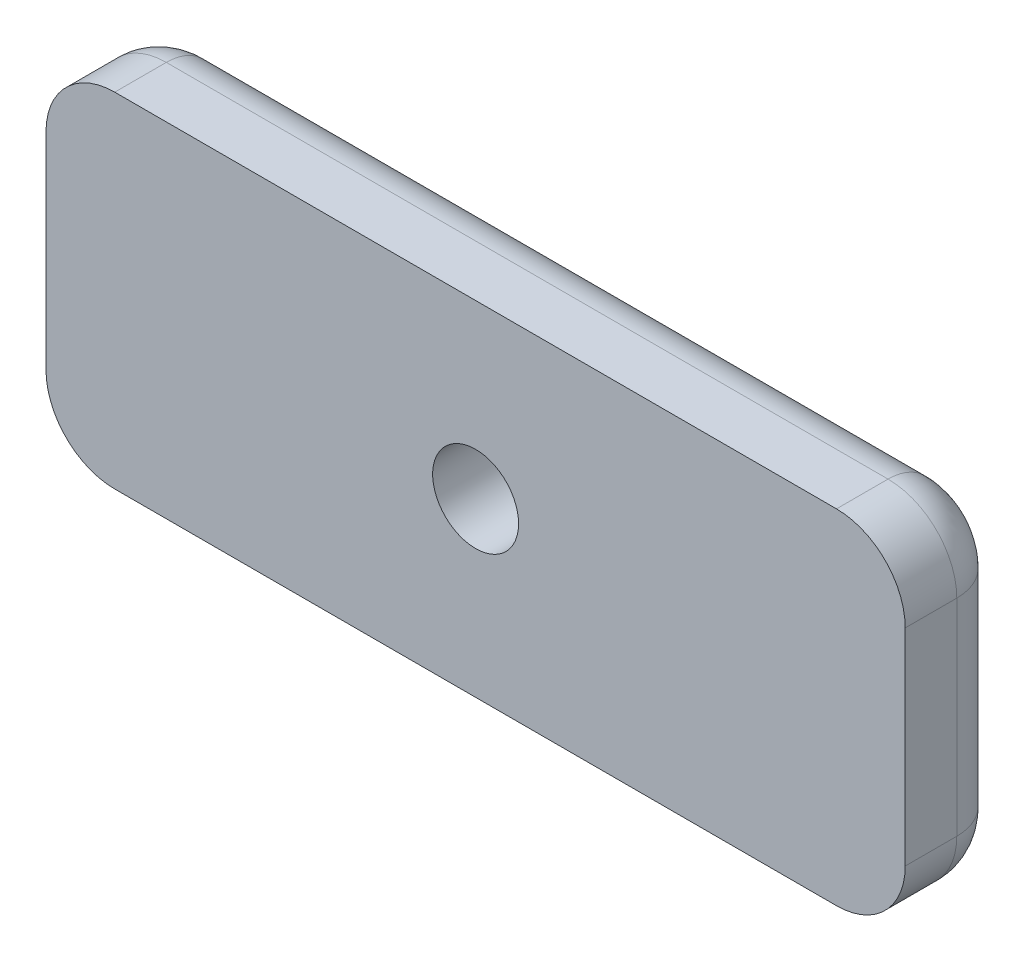
SolidWorks part; units mm, degrees
ref_plane "Front Plane" through (0, 0, 0) normal (0, 0, 1) x (1, 0, 0)
ref_plane "Top Plane" through (0, 0, 0) normal (0, 1, 0) x (1, 0, 0)
ref_plane "Right Plane" through (0, 0, 0) normal (1, 0, 0) x (0, 0, -1)
sketch "Sketch1" plane through (0, 0, 0) normal (0, 0, 1) x (1, 0, 0)
  line L1 (-21, 11.5842) -> (21, 11.5842)
  line L2 (-25, 7.5842) -> (-25, -4.4158)
  line L3 (-21, -8.4158) -> (21, -8.4158)
  line L4 (25, 7.5842) -> (25, -4.4158)
  arc A1 (21, 11.5842) -> (25, 7.5842) centre (21, 7.5842) cw
  arc A2 (21, -8.4158) -> (25, -4.4158) centre (21, -4.4158) ccw
  arc A3 (-25, -4.4158) -> (-21, -8.4158) centre (-21, -4.4158) ccw
  arc A4 (-21, 11.5842) -> (-25, 7.5842) centre (-21, 7.5842) ccw
  circle A5 centre (0, 1.5842) radius 2.5
  point P8 (25, 11.5842)
  point P11 (25, -8.4158)
  dimension "D5" = 4
  dimension "D2" = 20
extrude "Boss-Extrude1" add sketch "Sketch1" along normal blind 6
fillet "Fillet1" radius 3 8 edges at (23.8284, -7.2442, 0) (0, -8.4158, 0) (-23.8284, -7.2442, 0) (-25, 1.5842, 0) (-23.8284, 10.4126, 0) (0, 11.5842, 0) (23.8284, 10.4126, 0) (25, 1.5842, 0)
